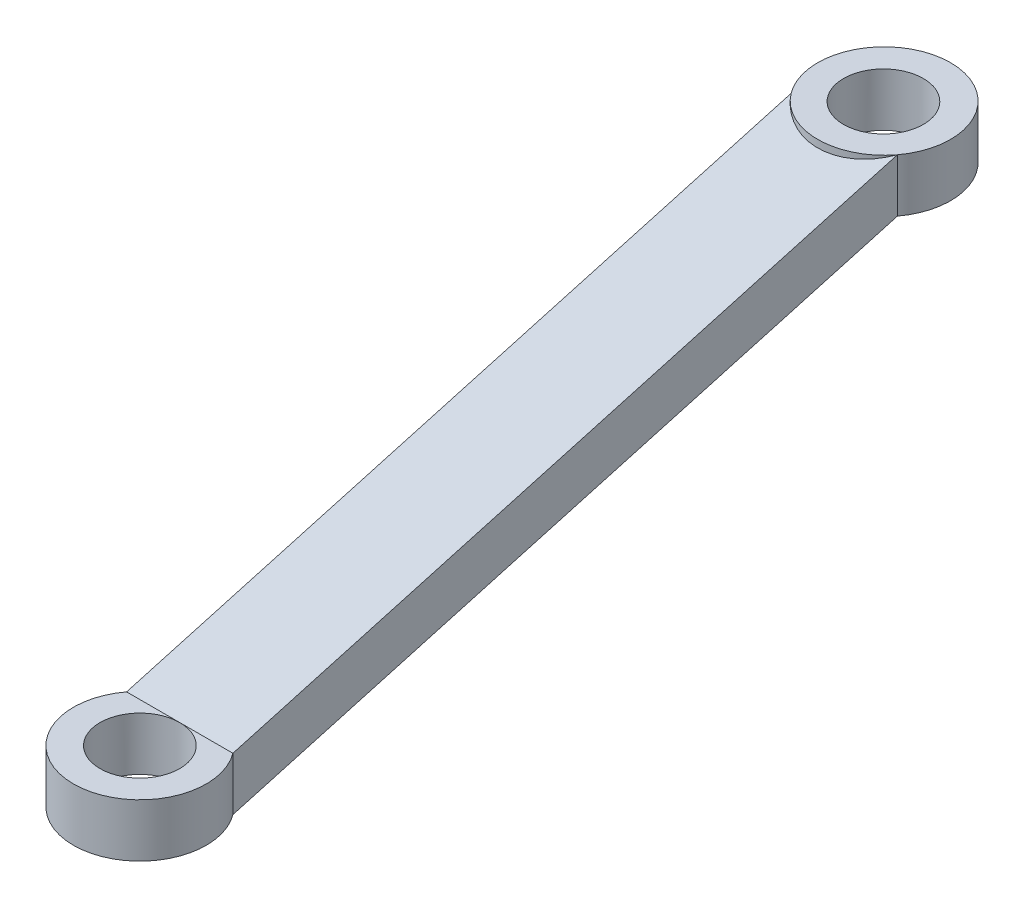
SolidWorks part; units mm, degrees
ref_plane "Front Plane" through (0, 0, 0) normal (0, 0, 1) x (1, 0, 0)
ref_plane "Top Plane" through (0, 0, 0) normal (0, 1, 0) x (1, 0, 0)
ref_plane "Right Plane" through (0, 0, 0) normal (1, 0, 0) x (0, 0, -1)
sketch "Sketch1" plane through (0, 0, 0) normal (1, 0, 0) x (0, 0, -1)
  line L0 (59.7041, 0) -> (-56.2867, 0) construction
  line L1 (0, 39.8696) -> (0, -65.0649) construction
  line L2 (0, 0) -> (0, 2)
  line L3 (0, 2) -> (25, 9)
  line L4 (25, 9) -> (25, 7)
  line L5 (25, 7) -> (0, 0)
  dimension "D1" = 25
  dimension "D2" = 9
  dimension "D3" = 2
extrude "Boss-Extrude1" add sketch "Sketch1" along normal blind 4
sketch "Sketch2" plane through (0, 0, 0) normal (0, 1, 0) x (1, 0, 0)
  circle A0 centre (2, -1.5) radius 2.5
  dimension "D1" = 5
extrude "Boss-Extrude2" add sketch "Sketch2" along normal up to vertex (2 mm away) up to point (4, 2, 0)
ref_plane "Plane1" through (0, 7, 0) normal (0, -1, 0) x (-1, 0, 0)
sketch "Sketch3" plane through (0, 7, 0) normal (0, -1, 0) x (-1, 0, 0)
  circle A0 centre (-2, 26.5) radius 2.5
  dimension "D1" = 5
extrude "Boss-Extrude3" add sketch "Sketch3" against normal up to vertex (2 mm away)
sketch "Sketch4" plane through (0, 2, 0) normal (0, 1, 0) x (1, 0, 0)
  circle A0 centre (2, -1.5) radius 2.5 construction
  circle A1 centre (2, -1.5) radius 1.5
  dimension "D1" = 3
extrude "Cut-Extrude1" cut sketch "Sketch4" against normal through all
sketch "Sketch5" plane through (0, 9, 0) normal (0, 1, 0) x (1, 0, 0)
  circle A0 centre (2.0015, 26.4733) radius 2.4733 construction
  circle A1 centre (2.0015, 26.4733) radius 1.5
  dimension "D1" = 3
extrude "Cut-Extrude2" cut sketch "Sketch5" against normal through all
